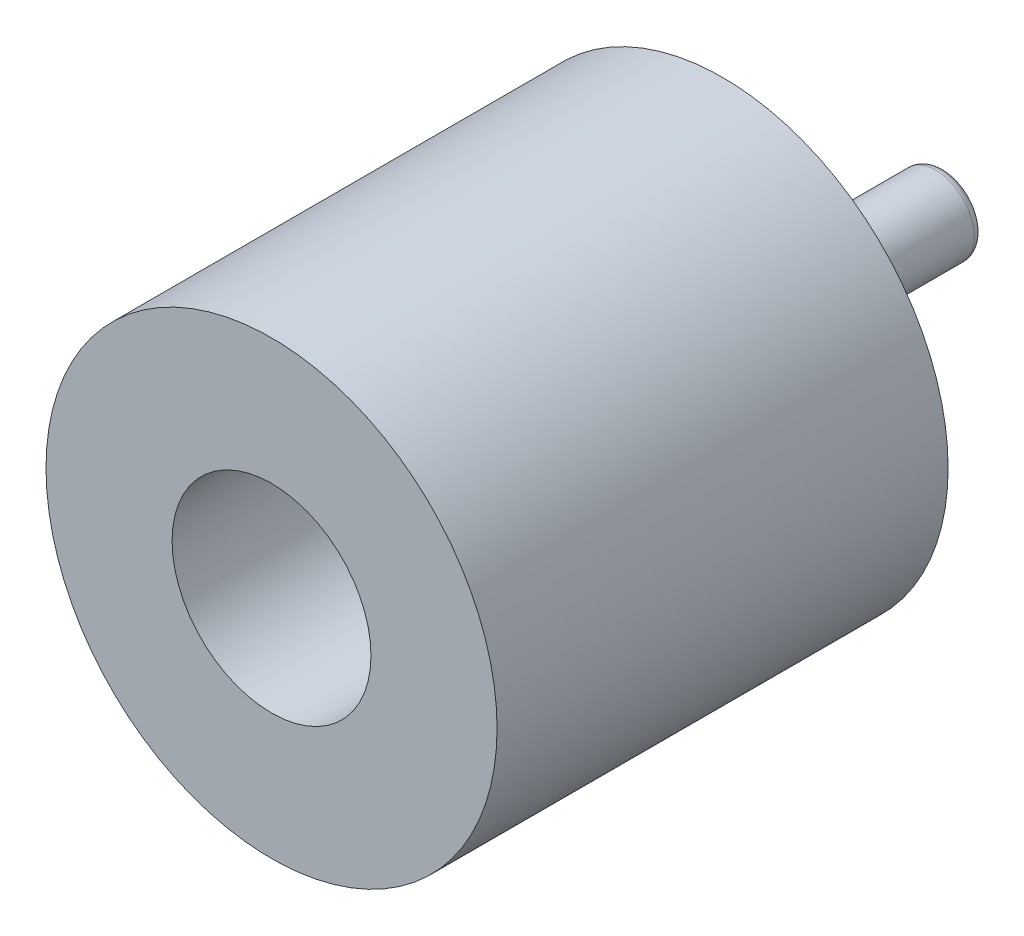
SolidWorks part; units mm, degrees
ref_plane "Front Plane" through (0, 0, 0) normal (0, 0, 1) x (1, 0, 0)
ref_plane "Top Plane" through (0, 0, 0) normal (0, 1, 0) x (1, 0, 0)
ref_plane "Right Plane" through (0, 0, 0) normal (1, 0, 0) x (0, 0, -1)
sketch "Sketch1" plane through (0, 0, 0) normal (0, 0, 1) x (1, 0, 0)
  circle A0 centre (0, 0) radius 2.54
  dimension "D1" = 5.08
extrude "Boss-Extrude1" add sketch "Sketch1" along normal blind 5.08
sketch "Sketch2" plane through (0, 0, 5.08) normal (0, 0, 1) x (1, 0, 0)
  circle A0 centre (0, 0) radius 1.12
  dimension "D1" = 2.24
extrude "Cut-Extrude1" cut sketch "Sketch2" against normal blind 3
sketch "Sketch3" plane through (0, 0, 0) normal (0, 0, -1) x (-1, 0, 0)
  circle A0 centre (0, 0) radius 0.435
  dimension "D1" = 0.87
extrude "Boss-Extrude2" add sketch "Sketch3" along normal blind 2.5
fillet "Fillet1" radius 0.1 1 edges at (-0.435, 0, 0)
fillet "Fillet2" radius 0.1 1 edges at (-0.435, 0, -2.5)
equation "\"D1@Boss-Extrude1\"=2mm"
equation "\"D1@Cut-Extrude1\"=3mm"
equation "\"D1@Sketch2\"=2.30-0.06mm"
